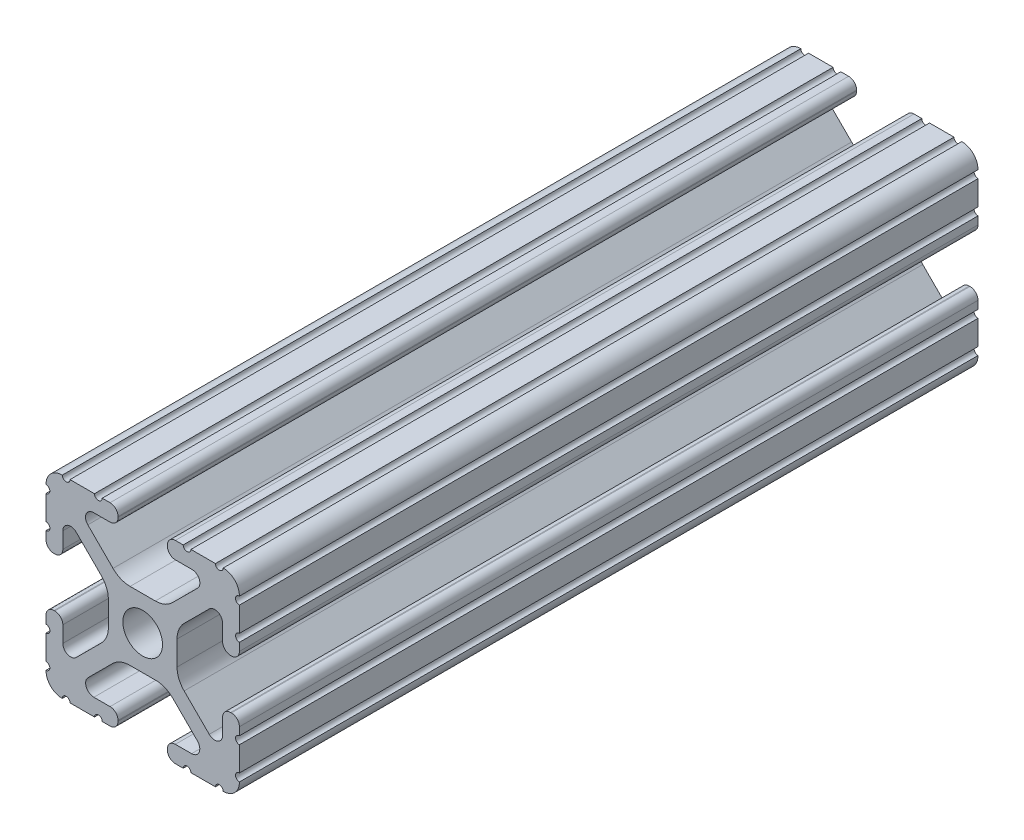
SolidWorks part; units mm, degrees
ref_plane "Front Plane" through (0, 0, 0) normal (0, 0, 1) x (1, 0, 0)
ref_plane "Top Plane" through (0, 0, 0) normal (0, 1, 0) x (1, 0, 0)
ref_plane "Right Plane" through (0, 0, 0) normal (1, 0, 0) x (0, 0, -1)
sketch "Sketch1" plane through (0, 0, 0) normal (0, 0, 1) x (1, 0, 0)
  line L0 (-7.207, 8.7244) -> (-3.8983, 5.4232)
  line L1 (-4.2875, 10.4902) -> (-6.4768, 10.4902)
  line L2 (-3.2385, 11.651) -> (-3.2385, 11.5392)
  line L3 (-5.3171, 12.7) -> (-4.2875, 12.7)
  line L4 (0, 13.4005) -> (0, -14.8534) construction
  line L5 (12.7, 0) -> (-13.9989, 0) construction
  line L6 (-9.5504, 12.7) -> (-6.3331, 12.7)
  line L7 (-12.7, 6.3331) -> (-12.7, 9.5504)
  line L8 (-12.7, 4.2875) -> (-12.7, 5.3171)
  line L9 (-11.5392, 3.2385) -> (-11.651, 3.2385)
  line L10 (-10.4902, 6.4021) -> (-10.4902, 4.2875)
  line L11 (-5.441, 3.8408) -> (-8.7371, 7.1294)
  line L12 (-4.5085, -1.5932) -> (-4.5085, 1.5932)
  line L13 (-1.7093, -4.4958) -> (1.7093, -4.4958)
  line L14 (3.9523, -5.4237) -> (7.1797, -8.6452)
  line L15 (6.4164, -10.4902) -> (4.2875, -10.4902)
  line L16 (3.2385, -11.5392) -> (3.2385, -11.651)
  line L17 (4.2875, -12.7) -> (5.3171, -12.7)
  line L18 (6.3331, -12.7) -> (9.5504, -12.7)
  line L19 (12.7, -9.5504) -> (12.7, -6.3331)
  line L20 (12.7, -5.3171) -> (12.7, -4.2875)
  line L21 (11.651, -3.2385) -> (11.5392, -3.2385)
  line L22 (10.4902, -4.2875) -> (10.4902, -6.4021)
  line L23 (8.7371, -7.1294) -> (5.441, -3.8408)
  line L24 (4.5085, -1.5932) -> (4.5085, 1.5932)
  line L25 (5.441, 3.8408) -> (8.7371, 7.1294)
  line L26 (10.4902, 6.4021) -> (10.4902, 4.2875)
  line L27 (11.5392, 3.2385) -> (11.651, 3.2385)
  line L28 (12.7, 4.2875) -> (12.7, 5.3171)
  line L29 (12.7, 6.3331) -> (12.7, 9.5504)
  line L30 (9.5504, 12.7) -> (6.3331, 12.7)
  line L31 (5.3171, 12.7) -> (4.2875, 12.7)
  line L32 (3.2385, 11.651) -> (3.2385, 11.5392)
  line L33 (4.2875, 10.4902) -> (6.4768, 10.4902)
  line L34 (7.207, 8.7244) -> (3.8983, 5.4232)
  line L35 (1.6558, 4.4958) -> (-1.6558, 4.4958)
  line L36 (-8.7371, -7.1294) -> (-5.441, -3.8408)
  line L37 (-10.4902, -4.2875) -> (-10.4902, -6.4021)
  line L38 (-11.651, -3.2385) -> (-11.5392, -3.2385)
  line L39 (-12.7, -5.3171) -> (-12.7, -4.2875)
  line L40 (-12.7, -9.5504) -> (-12.7, -6.3331)
  line L41 (-6.3331, -12.7) -> (-9.5504, -12.7)
  line L42 (-4.2875, -12.7) -> (-5.3171, -12.7)
  line L43 (-3.2385, -11.5392) -> (-3.2385, -11.651)
  line L44 (-6.4164, -10.4902) -> (-4.2875, -10.4902)
  line L45 (-3.9523, -5.4237) -> (-7.1797, -8.6452)
  arc A0 (-7.207, 8.7244) -> (-6.4768, 10.4902) centre (-6.4768, 9.4563) cw
  arc A1 (-3.2385, 11.5392) -> (-4.2875, 10.4902) centre (-4.2875, 11.5392) cw
  arc A2 (-4.2875, 12.7) -> (-3.2385, 11.651) centre (-4.2875, 11.651) cw
  arc A3 (-5.3171, 12.7) -> (-6.3331, 12.7) centre (-5.8251, 12.7) cw
  arc A4 (-9.5504, 12.7) -> (-10.5664, 12.6998) centre (-10.0584, 12.7) cw
  arc A5 (-12.6998, 10.5664) -> (-10.5664, 12.6998) centre (-10.5918, 10.5918) cw
  arc A6 (-12.6998, 10.5664) -> (-12.7, 9.5504) centre (-12.7, 10.0584) cw
  arc A7 (-12.7, 6.3331) -> (-12.7, 5.3171) centre (-12.7, 5.8251) cw
  arc A8 (-11.651, 3.2385) -> (-12.7, 4.2875) centre (-11.651, 4.2875) cw
  arc A9 (-10.4902, 4.2875) -> (-11.5392, 3.2385) centre (-11.5392, 4.2875) cw
  circle A10 centre (0, 0) radius 2.6035
  arc A11 (-10.4902, 6.4021) -> (-8.7371, 7.1294) centre (-9.4628, 6.4021) cw
  arc A12 (-5.441, 3.8408) -> (-4.5085, 1.5932) centre (-7.6835, 1.5932) cw
  arc A13 (-4.5085, -1.5932) -> (-5.441, -3.8408) centre (-7.6835, -1.5932) cw
  arc A14 (-8.7371, -7.1294) -> (-10.4902, -6.4021) centre (-9.4628, -6.4021) cw
  arc A15 (-1.7093, -4.4958) -> (-3.9523, -5.4237) centre (-1.7093, -7.6708) ccw
  arc A16 (3.9523, -5.4237) -> (1.7093, -4.4958) centre (1.7093, -7.6708) ccw
  arc A17 (6.4164, -10.4902) -> (7.1797, -8.6452) centre (6.4164, -9.4098) ccw
  arc A18 (4.2875, -10.4902) -> (3.2385, -11.5392) centre (4.2875, -11.5392) ccw
  arc A19 (3.2385, -11.651) -> (4.2875, -12.7) centre (4.2875, -11.651) ccw
  arc A20 (6.3331, -12.7) -> (5.3171, -12.7) centre (5.8251, -12.7) ccw
  arc A21 (10.5664, -12.6998) -> (9.5504, -12.7) centre (10.0584, -12.7) ccw
  arc A22 (10.5664, -12.6998) -> (12.6998, -10.5664) centre (10.5918, -10.5918) ccw
  arc A23 (12.7, -9.5504) -> (12.6998, -10.5664) centre (12.7, -10.0584) ccw
  arc A24 (12.7, -5.3171) -> (12.7, -6.3331) centre (12.7, -5.8251) ccw
  arc A25 (12.7, -4.2875) -> (11.651, -3.2385) centre (11.651, -4.2875) ccw
  arc A26 (11.5392, -3.2385) -> (10.4902, -4.2875) centre (11.5392, -4.2875) ccw
  arc A27 (8.7371, -7.1294) -> (10.4902, -6.4021) centre (9.4628, -6.4021) ccw
  arc A28 (4.5085, -1.5932) -> (5.441, -3.8408) centre (7.6835, -1.5932) ccw
  arc A29 (5.441, 3.8408) -> (4.5085, 1.5932) centre (7.6835, 1.5932) ccw
  arc A30 (10.4902, 6.4021) -> (8.7371, 7.1294) centre (9.4628, 6.4021) ccw
  arc A31 (10.4902, 4.2875) -> (11.5392, 3.2385) centre (11.5392, 4.2875) ccw
  arc A32 (11.651, 3.2385) -> (12.7, 4.2875) centre (11.651, 4.2875) ccw
  arc A33 (12.7, 6.3331) -> (12.7, 5.3171) centre (12.7, 5.8251) ccw
  arc A34 (12.6998, 10.5664) -> (12.7, 9.5504) centre (12.7, 10.0584) ccw
  arc A35 (12.6998, 10.5664) -> (10.5664, 12.6998) centre (10.5918, 10.5918) ccw
  arc A36 (9.5504, 12.7) -> (10.5664, 12.6998) centre (10.0584, 12.7) ccw
  arc A37 (5.3171, 12.7) -> (6.3331, 12.7) centre (5.8251, 12.7) ccw
  arc A38 (4.2875, 12.7) -> (3.2385, 11.651) centre (4.2875, 11.651) ccw
  arc A39 (3.2385, 11.5392) -> (4.2875, 10.4902) centre (4.2875, 11.5392) ccw
  arc A40 (7.207, 8.7244) -> (6.4768, 10.4902) centre (6.4768, 9.4563) ccw
  arc A41 (1.6558, 4.4958) -> (3.8983, 5.4232) centre (1.6558, 7.6708) ccw
  arc A42 (-1.6558, 4.4958) -> (-3.8983, 5.4232) centre (-1.6558, 7.6708) cw
  arc A43 (-11.5392, -3.2385) -> (-10.4902, -4.2875) centre (-11.5392, -4.2875) cw
  arc A44 (-12.7, -4.2875) -> (-11.651, -3.2385) centre (-11.651, -4.2875) cw
  arc A45 (-12.7, -5.3171) -> (-12.7, -6.3331) centre (-12.7, -5.8251) cw
  arc A46 (-12.7, -9.5504) -> (-12.6998, -10.5664) centre (-12.7, -10.0584) cw
  arc A47 (-10.5664, -12.6998) -> (-12.6998, -10.5664) centre (-10.5918, -10.5918) cw
  arc A48 (-10.5664, -12.6998) -> (-9.5504, -12.7) centre (-10.0584, -12.7) cw
  arc A49 (-6.3331, -12.7) -> (-5.3171, -12.7) centre (-5.8251, -12.7) cw
  arc A50 (-3.2385, -11.651) -> (-4.2875, -12.7) centre (-4.2875, -11.651) cw
  arc A51 (-4.2875, -10.4902) -> (-3.2385, -11.5392) centre (-4.2875, -11.5392) cw
  arc A52 (-6.4164, -10.4902) -> (-7.1797, -8.6452) centre (-6.4164, -9.4098) cw
  dimension "D1" = 5.207
  dimension "D9" = 14.859
  dimension "D2" = 25.4
  dimension "D3" = 12.7
  dimension "D4" = 6.477
  dimension "D5" = 8.2042
  dimension "D6" = 9.017
  dimension "D8" = 2.2098
  dimension "D10" = 2.2098
extrude "Extrude1" add sketch "Sketch1" against normal blind 97
